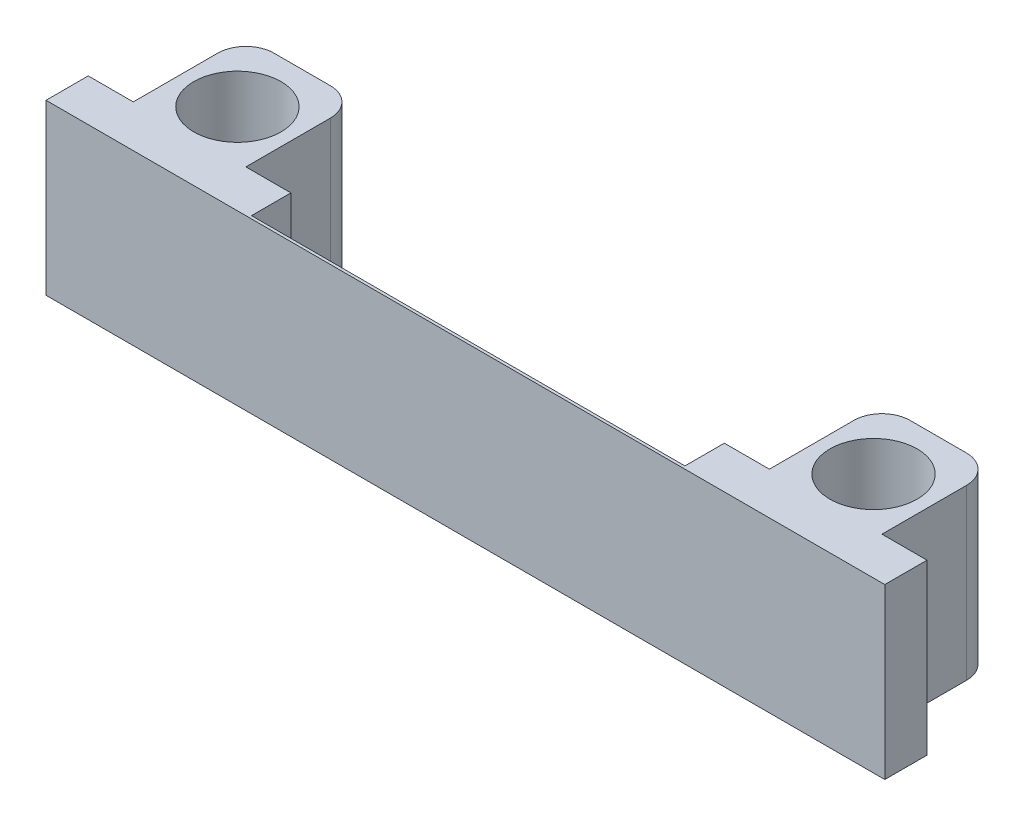
SolidWorks part; units mm, degrees
ref_plane "Front Plane" through (0, 0, 0) normal (0, 0, 1) x (1, 0, 0)
ref_plane "Top Plane" through (0, 0, 0) normal (0, 1, 0) x (1, 0, 0)
ref_plane "Right Plane" through (0, 0, 0) normal (1, 0, 0) x (0, 0, -1)
sketch "Sketch2" plane through (0, 0, 0) normal (0, 1, 0) x (1, 0, 0)
  line L0 (-14.8639, 0) -> (-6.8639, 0)
  line L1 (-6.8639, 0) -> (-6.8639, 20)
  line L2 (-6.8639, 20) -> (13.1361, 20)
  line L3 (13.1361, 20) -> (13.1361, 0)
  line L4 (13.1361, 0) -> (21.1361, 0)
  line L5 (21.1361, 0) -> (21.1361, -3)
  line L6 (21.1361, -3) -> (-14.8639, -3)
  line L7 (-14.8639, -3) -> (-14.8639, 0)
  dimension "D1" = 20
  dimension "D2" = 20
  dimension "D3" = 8
  dimension "D4" = 8
  dimension "D5" = 3
extrude "Boss-Extrude1" add sketch "Sketch2" along normal blind 30
sketch "Sketch3" plane through (0, 0, 0) normal (0, -1, 0) x (1, 0, 0)
  line L0 (3.1361, 3) -> (3.1361, -8.5) construction
  line L3 (-14.8639, 3) -> (21.1361, 3) construction
  circle A0 centre (3.1361, -8.5) radius 7.75
  dimension "D2" = 15.5
  dimension "D1" = 11.5
extrude "Cut-Extrude1" cut sketch "Sketch3" against normal blind 30
fillet "Fillet1" radius 5 2 edges at (13.1361, 15, -20) (-6.8639, 15, -20)
sketch "Sketch4" plane through (0, 0, 3) normal (0, 0, 1) x (1, 0, 0)
  line L1 (-14.8639, 30) -> (21.1361, 30)
  line L2 (-14.8639, 30) -> (-14.8639, 0)
  line L3 (-14.8639, 0) -> (21.1361, 0)
  line L4 (21.1361, 30) -> (21.1361, 0)
extrude "Boss-Extrude2" add sketch "Sketch4" along normal blind 4
move or copy body "Body-Move/Copy2" bodies to move or copy 103 copy yes number of copies 1 translate (113, 0, 0)
sketch "Sketch9" plane through (0, 0, 7) normal (0, 0, 1) x (1, 0, 0)
  line L1 (-14.8639, 30) -> (134.1361, 30)
  line L2 (-14.8639, 30) -> (-14.8639, 0)
  line L3 (-14.8639, 0) -> (134.1361, 0)
  line L4 (134.1361, 30) -> (134.1361, 0)
extrude "Boss-Extrude5" add sketch "Sketch9" along normal blind 0.5
